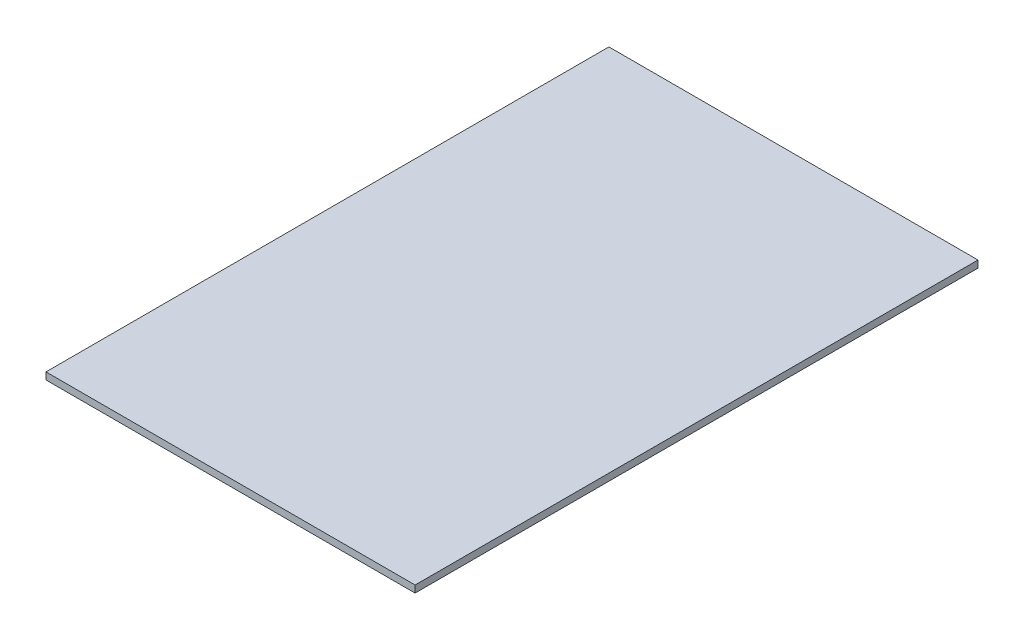
SolidWorks part; units mm, degrees
material "Oak"
ref_plane "Front" through (0, 0, 0) normal (0, 0, 1) x (1, 0, 0)
ref_plane "Top" through (0, 0, 0) normal (0, 1, 0) x (1, 0, 0)
ref_plane "Right" through (0, 0, 0) normal (1, 0, 0) x (0, 0, -1)
sketch "Sketch1" plane through (0, 0, 0) normal (0, 1, 0) x (1, 0, 0)
  line L0 (0, 762.5) -> (0, 0)
  line L1 (0, 0) -> (500, 0)
  line L2 (500, 0) -> (500, 762.5)
  line L3 (500, 762.5) -> (0, 762.5)
  dimension "D1" = 500
  dimension "D2" = 762.5
extrude "Boss-Extrude1" add sketch "Sketch1" along normal blind 9.525
